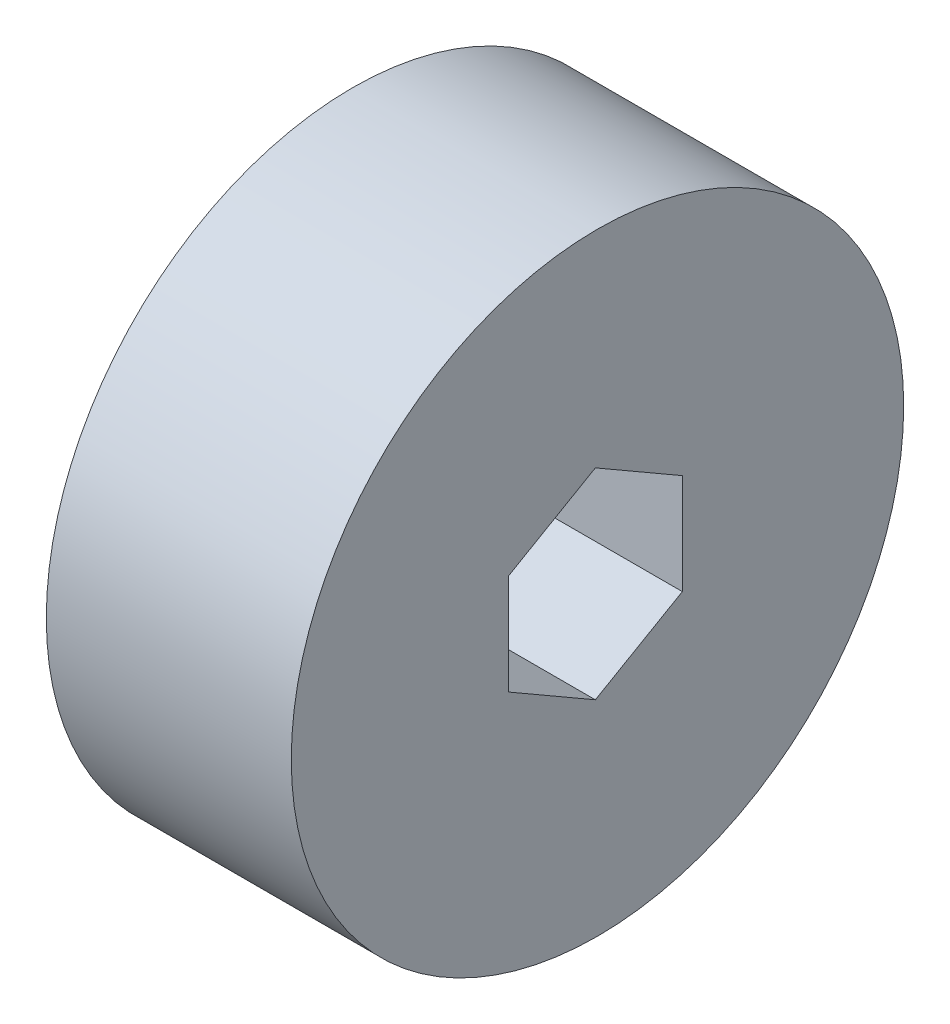
SolidWorks part; units mm, degrees
ref_plane "Front Plane" through (0, 0, 0) normal (0, 0, 1) x (1, 0, 0)
ref_plane "Top Plane" through (0, 0, 0) normal (0, 1, 0) x (1, 0, 0)
ref_plane "Right Plane" through (0, 0, 0) normal (1, 0, 0) x (0, 0, -1)
sketch "Sketch1" plane through (0, 0, 0) normal (1, 0, 0) x (0, 0, -1)
  line L6 (-0.0867, -4.0952) -> (3.4633, -2.0456)
  line L7 (3.4633, -2.0456) -> (3.4633, 2.0536)
  line L8 (3.4633, 2.0536) -> (-0.0867, 4.1032)
  line L9 (-0.0867, 4.1032) -> (-3.6367, 2.0536)
  line L10 (-3.6367, 2.0536) -> (-3.6367, -2.0456)
  line L11 (-3.6367, -2.0456) -> (-0.0867, -4.0952)
  circle A1 centre (0, 0) radius 12.5
  circle A2 centre (0, 0) radius 3.5031 construction
  point P1 (0, 0)
  point P9 (0, 0)
  point P13 (-0.0207, 0)
  dimension "D2" = 25
  dimension "D1" = 8.1984
extrude "Boss-Extrude1" add sketch "Sketch1" along normal mid plane 10
